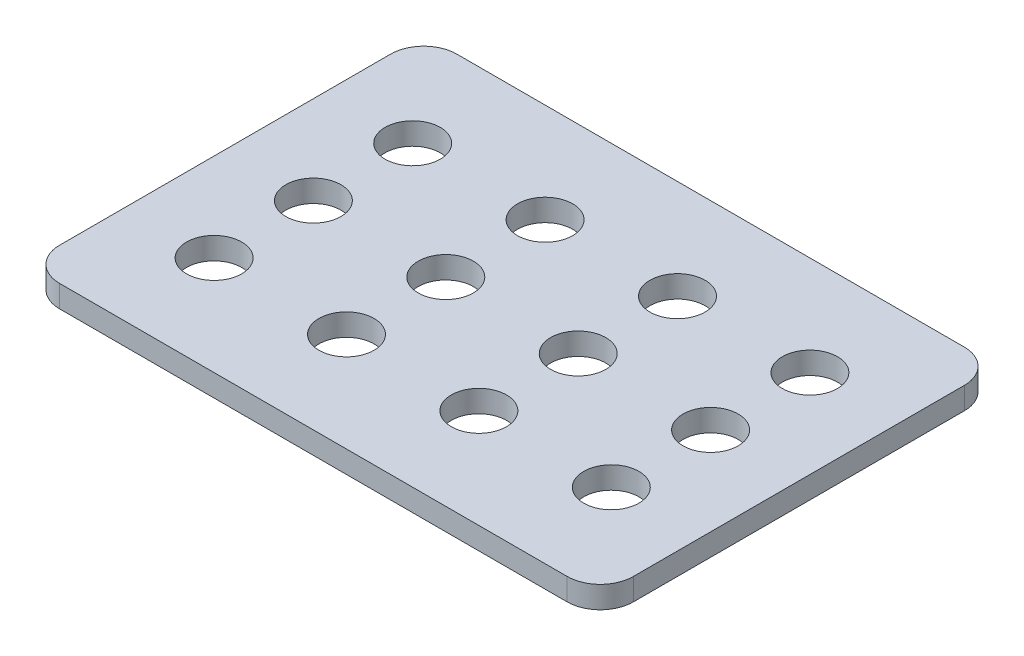
SolidWorks part; units mm, degrees
ref_plane "Front Plane" through (0, 0, 0) normal (0, 0, 1) x (1, 0, 0)
ref_plane "Top Plane" through (0, 0, 0) normal (0, 1, 0) x (1, 0, 0)
ref_plane "Right Plane" through (0, 0, 0) normal (1, 0, 0) x (0, 0, -1)
sketch "Sketch1" plane through (0, 0, 0) normal (0, 1, 0) x (1, 0, 0)
  line L0 (40, 187.4691) -> (40, -9.4801) construction
  line L1 (15, 0) -> (245, 0)
  line L2 (0, 15) -> (0, 165)
  line L3 (15, 180) -> (245, 180)
  line L4 (260, 15) -> (260, 165)
  circle A0 centre (40, 135) radius 12.5
  circle A1 centre (100, 135) radius 12.5
  circle A2 centre (160, 135) radius 12.5
  circle A3 centre (220, 135) radius 12.5
  circle A4 centre (100, 90) radius 12.5
  circle A5 centre (160, 90) radius 12.5
  circle A6 centre (220, 90) radius 12.5
  circle A7 centre (100, 45) radius 12.5
  circle A8 centre (160, 45) radius 12.5
  circle A9 centre (220, 45) radius 12.5
  circle A10 centre (40, 90) radius 12.5
  circle A11 centre (40, 45) radius 12.5
  arc A12 (15, 0) -> (0, 15) centre (15, 15) cw
  arc A13 (245, 0) -> (260, 15) centre (245, 15) ccw
  arc A14 (245, 180) -> (260, 165) centre (245, 165) cw
  arc A15 (0, 165) -> (15, 180) centre (15, 165) cw
  point P9 (0, 0)
  point P34 (0, 0)
  point P37 (260, 0)
  point P40 (260, 180)
  point P43 (0, 180)
  dimension "D1" = 25
  dimension "D11" = 15
  dimension "D2" = 180
  dimension "D3" = 260
  dimension "D4" = 40
  dimension "D5" = 45
  dimension "D8" = 45
  dimension "D9" = 60
  dimension "D10" = 40
  dimension "D6" = 4
  dimension "D7" = 3
extrude "Boss-Extrude1" add sketch "Sketch1" against normal blind 10
